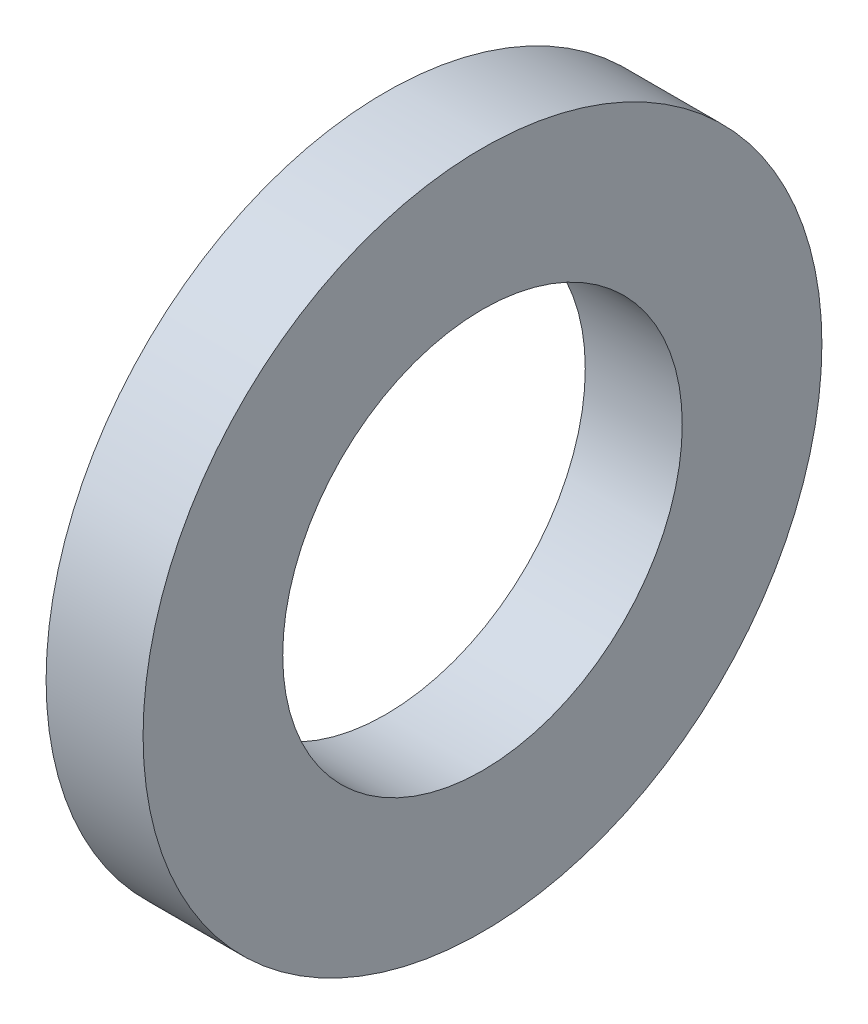
SolidWorks part; units mm, degrees
ref_plane "Front Plane" through (0, 0, 0) normal (0, 0, 1) x (1, 0, 0)
ref_plane "Top Plane" through (0, 0, 0) normal (0, 1, 0) x (1, 0, 0)
ref_plane "Right Plane" through (0, 0, 0) normal (1, 0, 0) x (0, 0, -1)
sketch "Sketch1" plane through (0, 0, 0) normal (1, 0, 0) x (0, 0, -1)
  circle A0 centre (0, 0) radius 6.5405
  circle A1 centre (0, 0) radius 11.1125
  dimension "D1" = 13.081
  dimension "D2" = 22.225
extrude "Boss-Extrude1" add sketch "Sketch1" along normal blind 3.175
